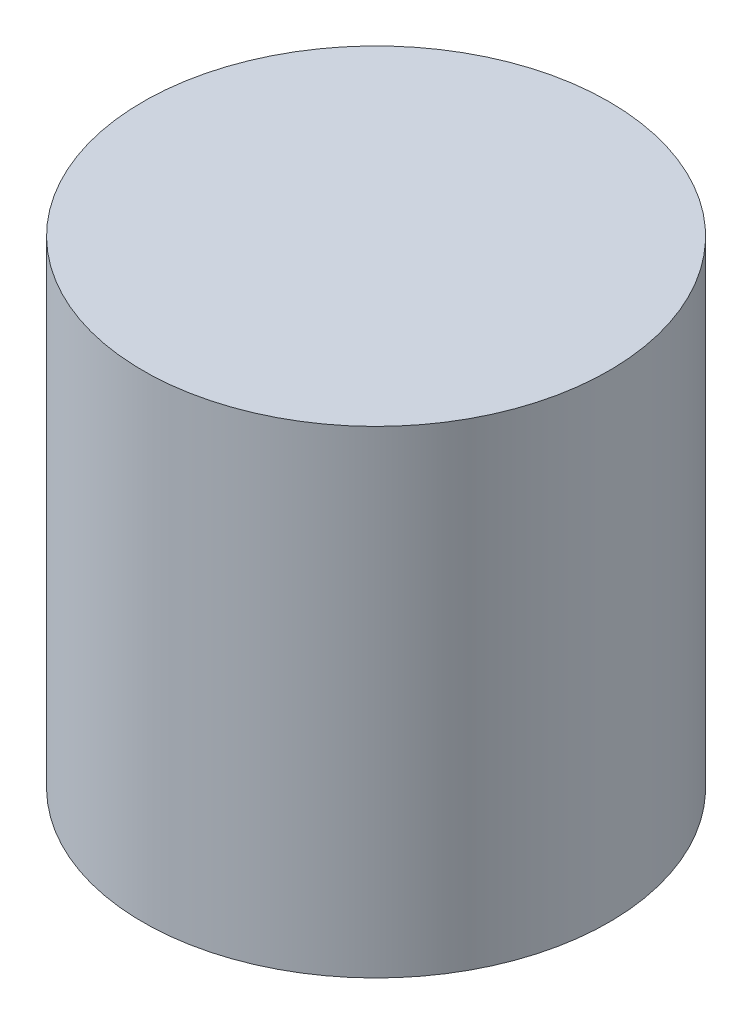
SolidWorks part; units mm, degrees
ref_plane "Front Plane" through (0, 0, 0) normal (0, 0, 1) x (1, 0, 0)
ref_plane "Top Plane" through (0, 0, 0) normal (0, 1, 0) x (1, 0, 0)
ref_plane "Right Plane" through (0, 0, 0) normal (1, 0, 0) x (0, 0, -1)
sketch "Sketch1" plane through (0, 0, 0) normal (0, 1, 0) x (1, 0, 0)
  circle A0 centre (0, 0) radius 200
extrude "Boss-Extrude1" add sketch "Sketch1" along normal blind 410
